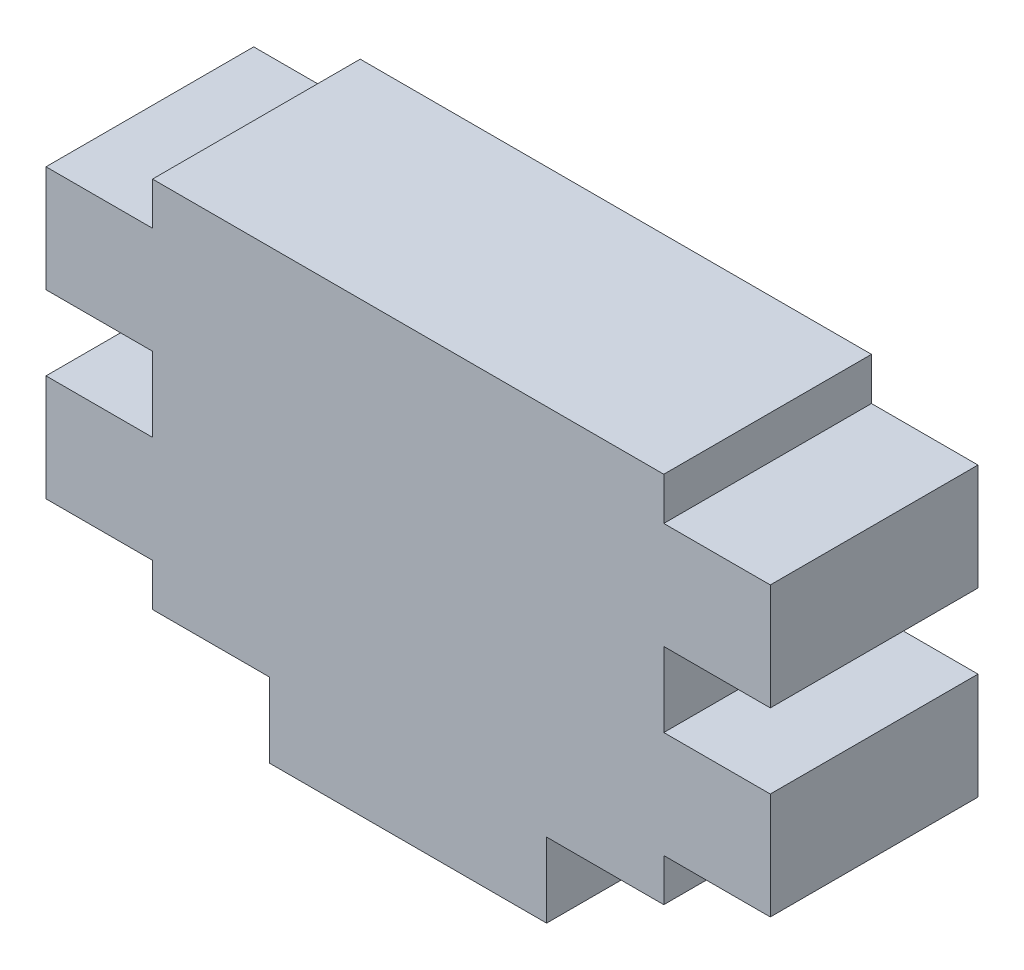
SolidWorks part; units mm, degrees
ref_plane "前视基准面" through (0, 0, 0) normal (0, 0, 1) x (1, 0, 0)
ref_plane "上视基准面" through (0, 0, 0) normal (0, 1, 0) x (1, 0, 0)
ref_plane "右视基准面" through (0, 0, 0) normal (1, 0, 0) x (0, 0, -1)
sketch "草图1" plane through (0, 0, 0) normal (0, 0, 1) x (1, 0, 0)
  line L0 (3.4, -1.35) -> (2.4, -1.35)
  line L1 (2.4, -1.35) -> (2.4, -1.75)
  line L2 (2.4, -1.75) -> (1.3, -1.75)
  line L3 (1.3, -1.75) -> (1.3, -2.4499)
  line L4 (1.3, -2.4499) -> (-1.3, -2.45)
  line L5 (-1.3, -2.45) -> (-1.3, -1.75)
  line L6 (-1.3, -1.75) -> (-2.4, -1.75)
  line L7 (-2.4, -1.75) -> (-2.4, -1.35)
  line L8 (-2.4, -1.35) -> (-3.4, -1.35)
  line L9 (-3.4, -1.35) -> (-3.4, -0.35)
  line L10 (-3.4, -0.35) -> (-2.4, -0.35)
  line L11 (-2.4, -0.35) -> (-2.4, 0.35)
  line L12 (-2.4, 0.35) -> (-3.4, 0.35)
  line L13 (-3.4, 0.35) -> (-3.4, 1.35)
  line L14 (-3.4, 1.35) -> (-2.4, 1.35)
  line L15 (-2.4, 1.35) -> (-2.4, 1.75)
  line L16 (-2.4, 1.75) -> (2.4, 1.75)
  line L17 (2.4, 1.75) -> (2.4, 1.35)
  line L18 (2.4, 1.35) -> (3.4, 1.35)
  line L19 (3.4, 1.35) -> (3.4, 0.35)
  line L20 (3.4, 0.35) -> (2.4, 0.35)
  line L21 (2.4, 0.35) -> (2.4, -0.35)
  line L22 (2.4, -0.35) -> (3.4, -0.35)
  line L23 (3.4, -0.35) -> (3.4, -1.35)
extrude "Component_Outline" add sketch "草图1" along normal blind 1.95 separate body
sketch3d "3D草图1"
  line L0 (0, 0, 0) -> (1, 0, 0)
  line L1 (0, 0, 0) -> (0, 1, 0)
  line L2 (0, 0, 0) -> (0, 0, 1)
  point P0 (0, 0, 0)
